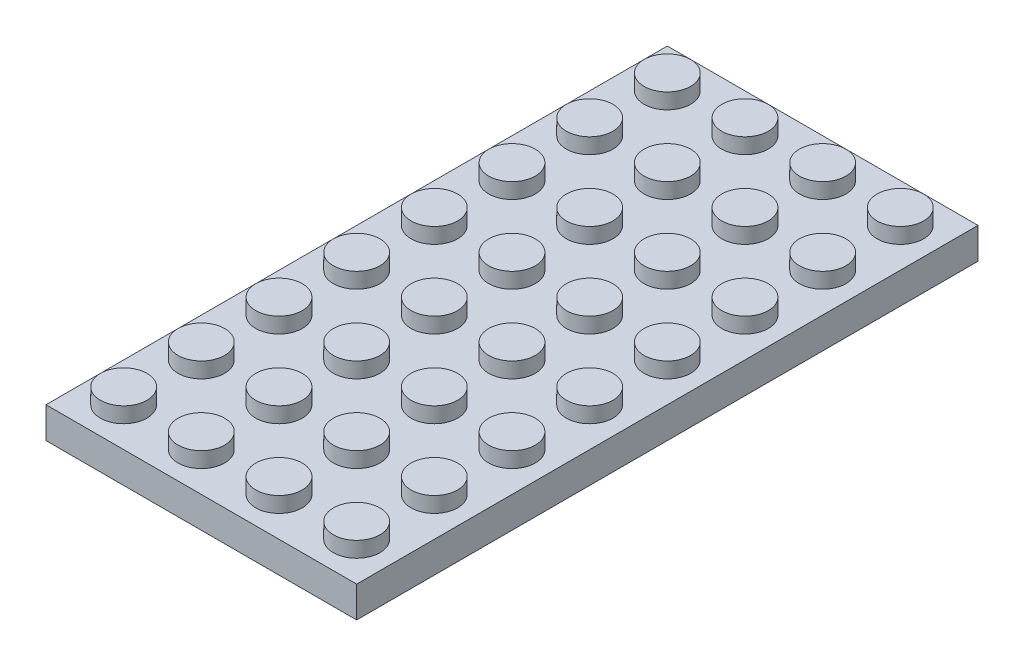
SolidWorks part; units mm, degrees
ref_plane "Front Plane" through (0, 0, 0) normal (0, 0, 1) x (1, 0, 0)
ref_plane "Top Plane" through (0, 0, 0) normal (0, 1, 0) x (1, 0, 0)
ref_plane "Right Plane" through (0, 0, 0) normal (1, 0, 0) x (0, 0, -1)
sketch "Sketch1" plane through (0, 0, 0) normal (0, 1, 0) x (1, 0, 0)
  line L1 (0, 0) -> (32, 0)
  line L2 (0, 0) -> (0, 64)
  line L3 (0, 64) -> (32, 64)
  line L4 (32, 0) -> (32, 64)
  dimension "D1" = 32
  dimension "D2" = 64
extrude "Boss-Extrude1" add sketch "Sketch1" along normal blind 3.2
sketch "Sketch2" plane through (0, 3.2, 0) normal (0, 1, 0) x (1, 0, 0)
  line L0 (16, 0) -> (16, 64) construction
  line L1 (0, 0) -> (32, 0) construction
  line L2 (32, 64) -> (0, 64) construction
  line L3 (32, 0) -> (32, 4) construction
  line L4 (32, 0) -> (32, 64) construction
  line L5 (32, 4) -> (28, 4) construction
  circle A0 centre (28, 4) radius 2.4
  dimension "D3" = 4.8
  dimension "D1" = 4
  dimension "D2" = 4
extrude "Boss-Extrude2" add sketch "Sketch2" along normal blind 1.6
pattern_linear "LPattern1" count 4 spacing 8 along (-1, 0, 0) count 8 spacing 8 along (0, 0, -1) of "Boss-Extrude2"
shell "Shell1" thickness 1.6
